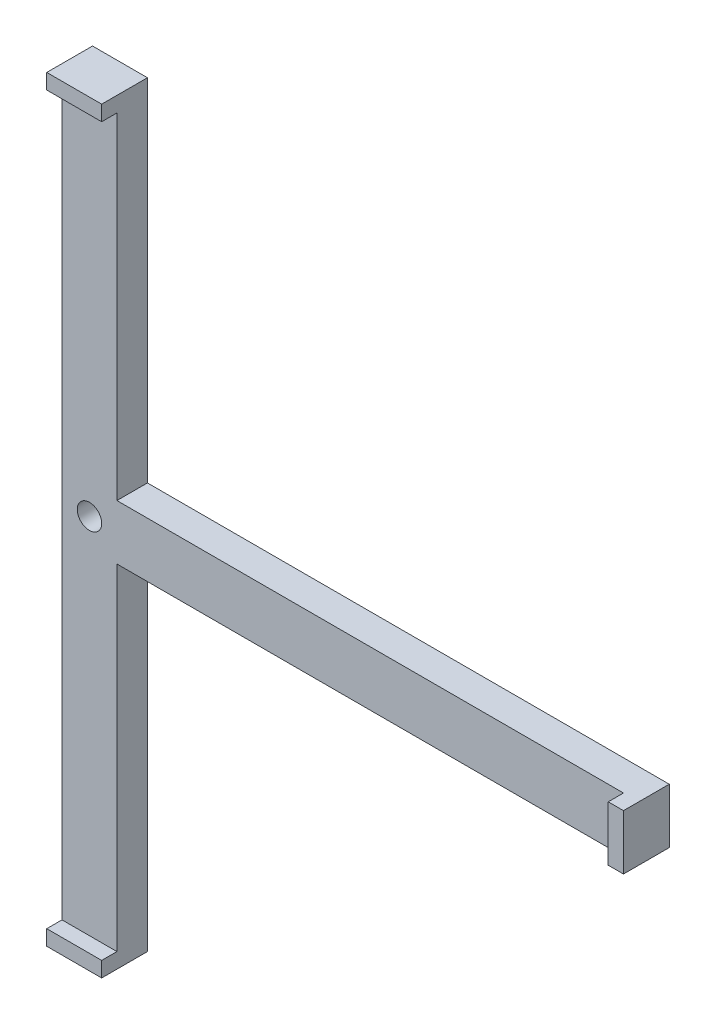
SolidWorks part; units mm, degrees
ref_plane "Front Plane" through (0, 0, 0) normal (0, 0, 1) x (1, 0, 0)
ref_plane "Top Plane" through (0, 0, 0) normal (0, 1, 0) x (1, 0, 0)
ref_plane "Right Plane" through (0, 0, 0) normal (1, 0, 0) x (0, 0, -1)
sketch "Sketch1" plane through (0, 0, 0) normal (0, 0, 1) x (1, 0, 0)
  line L0 (11.2026, -118.7516) -> (177.2026, -118.7516)
  line L1 (177.2026, -118.7516) -> (177.2026, -100.7516)
  line L2 (177.2026, -100.7516) -> (11.2026, -100.7516)
  line L3 (11.2026, -100.7516) -> (11.2026, 9.2484)
  line L4 (11.2026, 9.2484) -> (-6.7974, 9.2484)
  line L5 (-6.7974, 9.2484) -> (-6.7974, -228.7516)
  line L6 (-6.7974, -228.7516) -> (11.2026, -228.7516)
  line L7 (11.2026, -228.7516) -> (11.2026, -118.7516)
  line L8 (177.2026, -109.7516) -> (2.2026, -109.7516) construction
  circle A0 centre (2.2026, -109.7516) radius 4
  point P10 (2.2026, 9.2484)
  dimension "D5" = 8
  dimension "D1" = 175
  dimension "D2" = 18
  dimension "D3" = 18
  dimension "D4" = 110
extrude "Boss-Extrude1" add sketch "Sketch1" along normal blind 10
sketch "Sketch2" plane through (0, 0, 0) normal (0, 0, -1) x (-1, 0, 0)
  line L0 (6.7974, -228.7516) -> (-11.2026, -228.7516) construction
  line L1 (-177.2026, -118.7516) -> (-177.2026, -100.7516) construction
  line L2 (-11.2026, 9.2484) -> (6.7974, 9.2484) construction
  line L3 (6.7974, -228.7516) -> (-11.2026, -228.7516)
  line L4 (-177.2026, -118.7516) -> (-177.2026, -100.7516)
  line L5 (-11.2026, 9.2484) -> (6.7974, 9.2484)
  line L6 (6.7974, 9.2484) -> (6.7974, 14.2484)
  line L7 (6.7974, 14.2484) -> (-11.2026, 14.2484)
  line L8 (-11.2026, 14.2484) -> (-11.2026, 9.2484)
  line L9 (-177.2026, -100.7516) -> (-182.2026, -100.7516)
  line L10 (-182.2026, -100.7516) -> (-182.2026, -118.7516)
  line L11 (-182.2026, -118.7516) -> (-177.2026, -118.7516)
  line L12 (6.7974, -228.7516) -> (6.7974, -233.7516)
  line L13 (6.7974, -233.7516) -> (-11.2026, -233.7516)
  line L14 (-11.2026, -233.7516) -> (-11.2026, -228.7516)
  dimension "D1" = 5
extrude "Boss-Extrude2" add sketch "Sketch2" against normal blind 15
